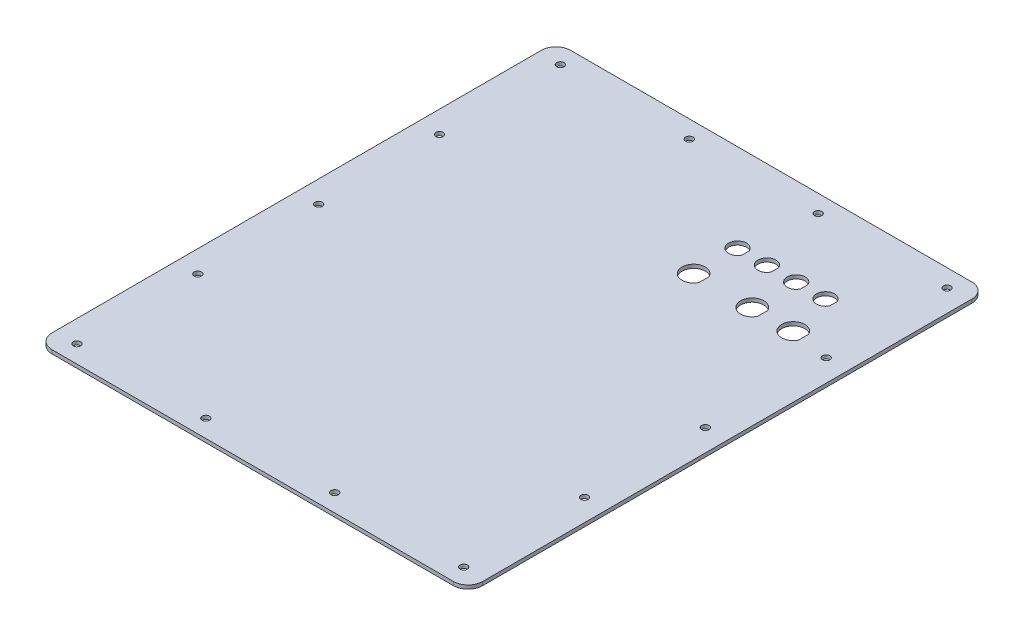
SolidWorks part; units mm, degrees
material "Acrylic (Medium-high impact)"
ref_plane "Front Plane" through (0, 0, 0) normal (0, 0, 1) x (1, 0, 0)
ref_plane "Top Plane" through (0, 0, 0) normal (0, 1, 0) x (1, 0, 0)
ref_plane "Right Plane" through (0, 0, 0) normal (1, 0, 0) x (0, 0, -1)
sketch "Sketch1" plane through (0, 0, 0) normal (0, 1, 0) x (1, 0, 0)
  line L1 (-186.69, -224.79) -> (186.69, -224.79)
  line L2 (-186.69, -224.79) -> (-186.69, 224.79)
  line L3 (-186.69, 224.79) -> (186.69, 224.79)
  line L4 (186.69, -224.79) -> (186.69, 224.79)
  line L5 (-186.69, -224.79) -> (186.69, 224.79) construction
  line L6 (-186.69, 224.79) -> (186.69, -224.79) construction
  point P0 (0, 0)
  dimension "D1" = 373.38
  dimension "D2" = 449.58
extrude "Boss-Extrude1" add sketch "Sketch1" along normal mid plane 3.175
fillet "Fillet1" radius 12.7 4 edges at (-186.69, 0, -224.79) (186.69, 0, -224.79) (186.69, 0, 224.79) (-186.69, 0, 224.79)
sketch "Sketch2" plane through (0, 1.5875, 0) normal (0, 1, 0) x (1, 0, 0)
  line L0 (-186.69, 209.55) -> (186.69, 209.55) construction
  line L1 (-186.69, 212.09) -> (-186.69, -212.09) construction
  line L2 (186.69, -212.09) -> (186.69, 212.09) construction
  line L3 (-167.64, 224.79) -> (-167.64, -224.79) construction
  line L4 (173.99, 224.79) -> (-173.99, 224.79) construction
  line L5 (-173.99, -224.79) -> (173.99, -224.79) construction
  circle A0 centre (-167.64, 209.55) radius 3.175
  point P12 (-167.64, 209.55)
  dimension "D3" = 6.35
  dimension "D1" = 15.24
  dimension "D2" = 19.05
extrude "Cut-Extrude1" cut sketch "Sketch2" against normal through all
pattern_linear "LPattern1" count 4 spacing 111.76 along (1, 0, 0) count 5 spacing 104.775 along (0, 0, 1) skipping (1, 1), (1, 2), (1, 3), (2, 1), (2, 2), (2, 3) of "Cut-Extrude1"
extrude "Cut-Extrude2" cut sketch "Sketch3" against normal through all
sketch "Sketch3" plane through (13.5601, 17.4625, -1.1968) normal (0, 1, 0) x (1, 0, 0)
  line L7 (128.8069, 104.8938) -> (128.8069, 113.6926)
  line L8 (116.6657, 144.1508) -> (116.6657, 150.6357)
  line L9 (91.2657, 144.1508) -> (91.2657, 150.6357)
  line L10 (93.2469, 104.8938) -> (93.2469, 113.6926)
  line L11 (65.8657, 144.1508) -> (65.8657, 150.6357)
  line L12 (40.4657, 144.1508) -> (40.4657, 150.6357)
  line L13 (42.4469, 104.8938) -> (42.4469, 113.6926)
  arc A7 (128.8069, 113.6926) -> (128.8069, 104.8938) centre (119.7899, 109.2932) ccw
  arc A8 (116.6657, 150.6357) -> (116.6657, 144.1508) centre (109.6299, 147.3932) ccw
  arc A9 (91.2657, 150.6357) -> (91.2657, 144.1508) centre (84.2299, 147.3932) ccw
  arc A10 (93.2469, 113.6926) -> (93.2469, 104.8938) centre (84.2299, 109.2932) ccw
  arc A11 (65.8657, 150.6357) -> (65.8657, 144.1508) centre (58.8299, 147.3932) ccw
  arc A12 (40.4657, 150.6357) -> (40.4657, 144.1508) centre (33.4299, 147.3932) ccw
  arc A13 (42.4469, 113.6926) -> (42.4469, 104.8938) centre (33.4299, 109.2932) ccw
